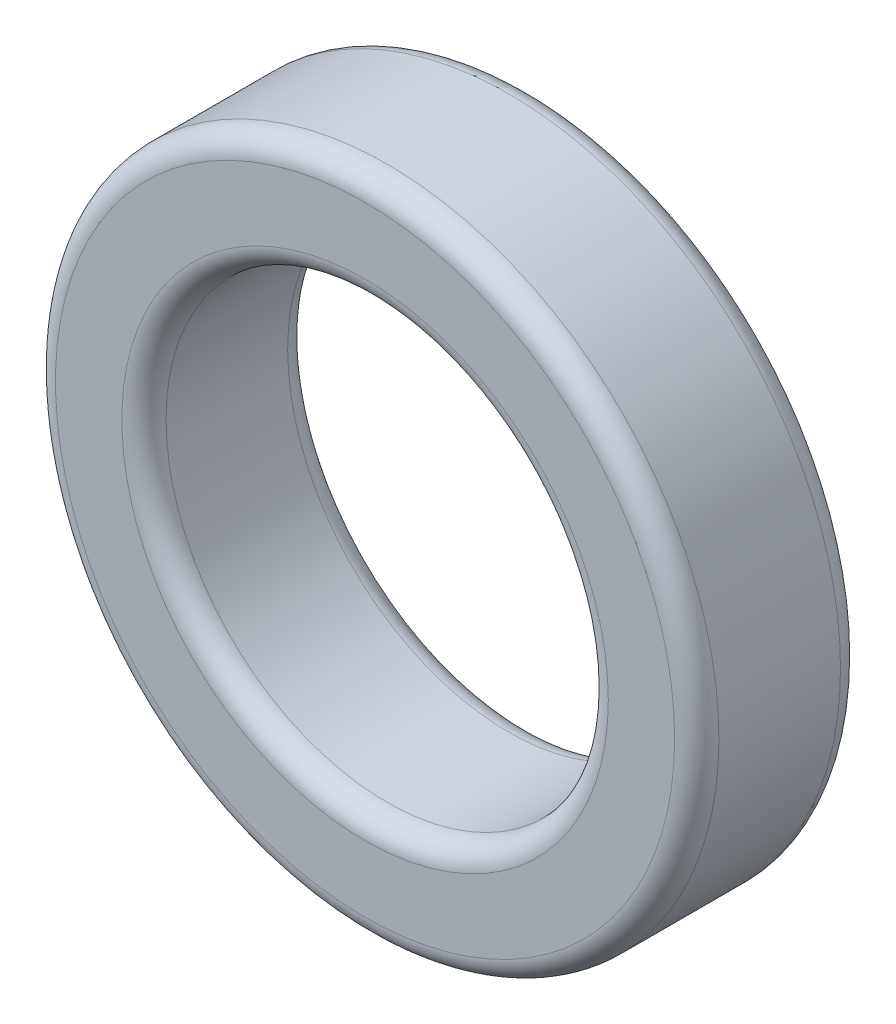
SolidWorks part; units mm, degrees
ref_plane "Front Plane" through (0, 0, 0) normal (0, 0, 1) x (1, 0, 0)
ref_plane "Top Plane" through (0, 0, 0) normal (0, 1, 0) x (1, 0, 0)
ref_plane "Right Plane" through (0, 0, 0) normal (1, 0, 0) x (0, 0, -1)
sketch "Sketch2" plane through (0, 0, 0) normal (0, 0, 1) x (1, 0, 0)
  circle A0 centre (0, 0) radius 5.08
  circle A1 centre (0, 0) radius 7.62
  dimension "D1" = 10.16
  dimension "D2" = 15.24
extrude "Boss-Extrude1" add sketch "Sketch2" along normal blind 3.81
fillet "Fillet1" radius 0.508 1 edges at (5.08, 0, 3.81)
fillet "Fillet2" radius 0.508 1 edges at (5.08, 0, 0)
fillet "Fillet3" radius 0.508 1 edges at (7.62, 0, 0)
fillet "Fillet4" radius 0.508 1 edges at (7.62, 0, 3.81)
